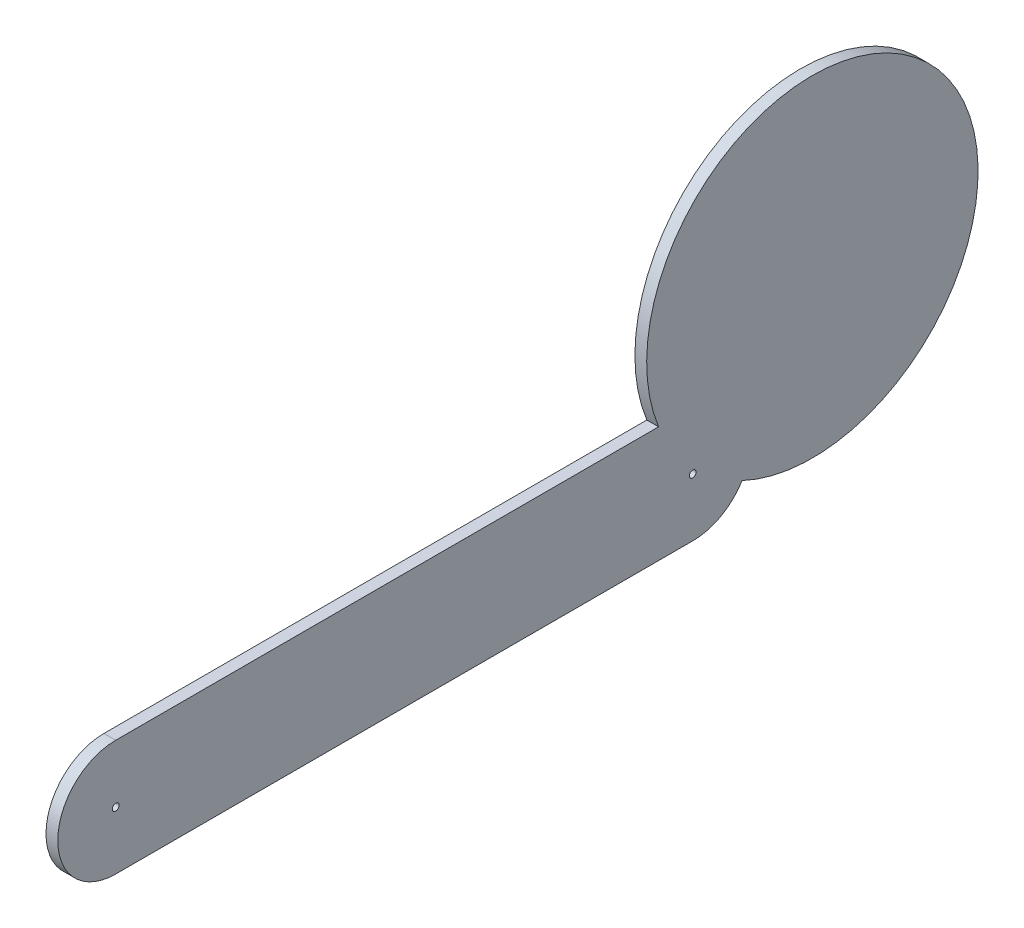
SolidWorks part; units mm, degrees
ref_plane "Front Plane" through (0, 0, 0) normal (0, 0, 1) x (1, 0, 0)
ref_plane "Top Plane" through (0, 0, 0) normal (0, 1, 0) x (1, 0, 0)
ref_plane "Right Plane" through (0, 0, 0) normal (1, 0, 0) x (0, 0, -1)
sketch "Sketch1" plane through (0, 0, 0) normal (1, 0, 0) x (0, 0, -1)
  line L0 (-134.8517, 37.2101) -> (114.1483, 37.2101)
  line L1 (114.1483, -12.7899) -> (-134.8517, -12.7899)
  arc A0 (-134.8517, -12.7899) -> (-134.8517, 37.2101) centre (-134.8517, 12.2101) cw
  arc A1 (114.1483, -12.7899) -> (114.1483, 37.2101) centre (114.1483, 12.2101) ccw
  circle A2 centre (-134.8517, 12.2101) radius 1.4732
  circle A3 centre (114.1483, 12.2101) radius 1.4732
  dimension "D3" = 2.9464
  dimension "D4" = 2.9464
  dimension "D1" = 249
  dimension "D2" = 50
extrude "Boss-Extrude1" add sketch "Sketch1" along normal blind 5.08
sketch "Sketch2" plane through (5.08, 0, 0) normal (1, 0, 0) x (0, 0, -1)
  line L0 (141.9062, 39.968) -> (186.8251, 84.8868) construction
  circle A0 centre (114.1483, 12.2101) radius 1.4732 construction
  circle A1 centre (165.7671, 63.8289) radius 71.5
  point P0 (114.2876, 10.7435)
  point P1 (114.1483, 12.2101)
  point P7 (165.7671, 63.8289)
  dimension "D2" = 143
  dimension "D1" = 73
extrude "Boss-Extrude2" add sketch "Sketch2" against normal blind 5.08
